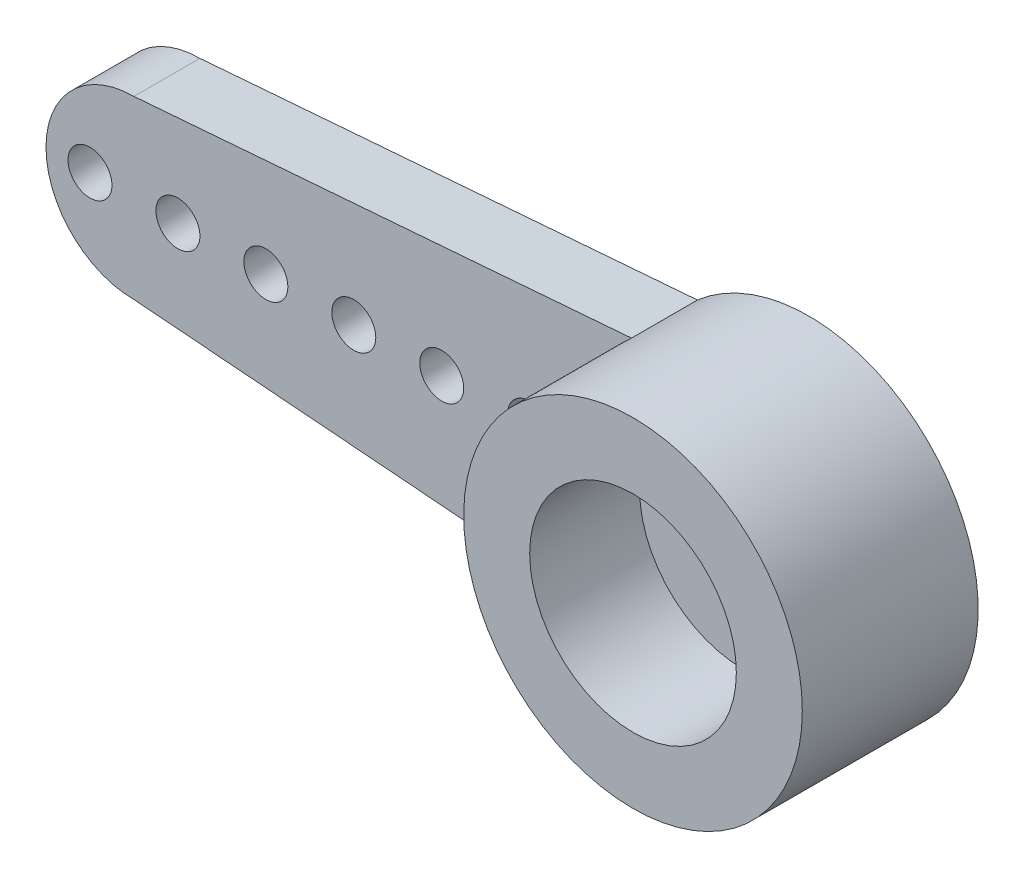
SolidWorks part; units mm, degrees
ref_plane "Piano frontale" through (0, 0, 0) normal (0, 0, 1) x (1, 0, 0)
ref_plane "Piano superiore" through (0, 0, 0) normal (0, 1, 0) x (1, 0, 0)
ref_plane "Piano destro" through (0, 0, 0) normal (1, 0, 0) x (0, 0, -1)
sketch "Schizzo1" plane through (0, 0, 0) normal (0, 0, 1) x (1, 0, 0)
  circle A0 centre (0, 0) radius 2.35
  circle A1 centre (0, 0) radius 3.85
  dimension "D1" = 4.7
  dimension "D2" = 1.5
extrude "Estrusione-Estrusione1" add sketch "Schizzo1" along normal blind 4
sketch "Schizzo3" plane through (0, 0, 0) normal (0, 0, -1) x (-1, 0, 0)
  line L1 (0, 3.85) -> (0, 2.35) construction
  line L2 (0, -2.35) -> (0, -3.85) construction
  line L4 (0, 3.1) -> (13.85, 2)
  line L5 (0, -3.1) -> (13.85, -2)
  arc A0 (13.85, -2) -> (13.85, 2) centre (13.85, 0) ccw
  circle A1 centre (0, 0) radius 3.85 construction
  arc A2 (0, 3.1) -> (0, -3.1) centre (0, 0) ccw
  circle A4 centre (0, 0) radius 3.85 construction
  circle A5 centre (0, 0) radius 2.35 construction
  point P2 (15.85, 0)
  point P3 (3.85, 0)
  dimension "D1" = 4
  dimension "D2" = 12
extrude "Estrusione-Estrusione2" add sketch "Schizzo3" against normal blind 1.5
sketch "Schizzo4" plane through (0, 0, 1.5) normal (0, 0, 1) x (1, 0, 0)
  line L0 (-3.85, 0) -> (-15.85, 0) construction
  arc A0 (-2.5337, 2.8988) -> (-2.5337, -2.8988) centre (0, 0) ccw construction
  arc A1 (-13.85, 2) -> (-13.85, -2) centre (-13.85, 0) ccw construction
  circle A2 centre (-4.85, 0) radius 0.5
  circle A3 centre (-6.85, 0) radius 0.5
  circle A4 centre (-8.85, 0) radius 0.5
  circle A5 centre (-10.85, 0) radius 0.5
  circle A6 centre (-12.85, 0) radius 0.5
  circle A7 centre (-14.85, 0) radius 0.5
  dimension "D1" = 1
  dimension "D2" = 6
extrude "Taglio-Estrusione1" cut sketch "Schizzo4" against normal up to next
